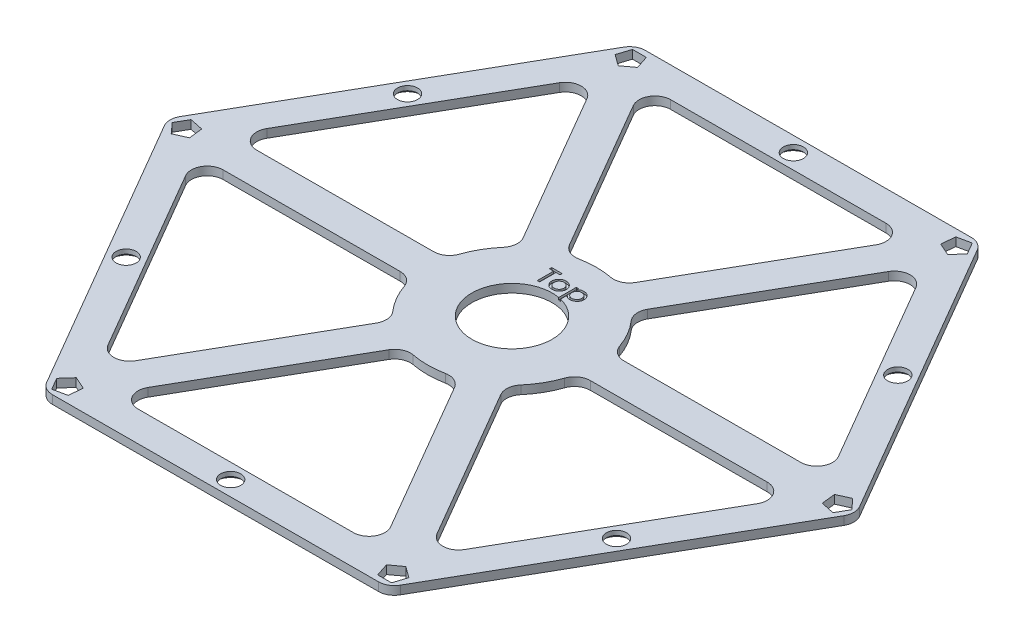
SolidWorks part; units mm, degrees
ref_plane "Front Plane" through (0, 0, 0) normal (0, 0, 1) x (1, 0, 0)
ref_plane "Top Plane" through (0, 0, 0) normal (0, 1, 0) x (1, 0, 0)
ref_plane "Right Plane" through (0, 0, 0) normal (1, 0, 0) x (0, 0, -1)
sketch "Sketch1" plane through (0, 0, 0) normal (0, 1, 0) x (1, 0, 0)
  line L0 (-31.0118, 53.34) -> (-30.9795, 42.6969) construction
  line L1 (-32.6705, 56.1929) -> (-64.9997, -0.197)
  line L2 (-64.9997, -0.197) -> (-32.3292, -56.3899)
  line L3 (-32.3292, -56.3899) -> (32.6705, -56.1929)
  line L4 (32.6705, -56.1929) -> (64.9997, 0.197)
  line L5 (64.9997, 0.197) -> (32.3292, 56.3899)
  line L6 (32.3292, 56.3899) -> (-32.6705, 56.1929)
  line L7 (-31.1934, 47.2773) -> (-56.5594, 3.0329)
  line L8 (-56.54, -3.3757) -> (-30.9063, -47.4655)
  line L9 (-25.3466, -50.6529) -> (25.6532, -50.4984)
  line L10 (31.1934, -47.2773) -> (56.5594, -3.0329)
  line L11 (56.54, 3.3757) -> (30.9063, 47.4655)
  line L12 (25.3466, 50.6529) -> (-25.6532, 50.4984)
  line L13 (-31.0118, 53.34) -> (-61.6997, -0.187) construction
  line L14 (-61.6997, -0.187) -> (-30.6879, -53.527) construction
  line L15 (-30.6879, -53.527) -> (31.0118, -53.34) construction
  line L16 (31.0118, -53.34) -> (61.6997, 0.187) construction
  line L17 (61.6997, 0.187) -> (30.6879, 53.527) construction
  line L18 (30.6879, 53.527) -> (-31.0118, 53.34) construction
  line L50 (28.7645, 52.4087) -> (31.1571, 51.3521)
  line L51 (-31.0051, 51.1151) -> (-28.8937, 52.6589)
  line L52 (-28.8937, 52.6589) -> (-29.7095, 55.144)
  line L58 (-31.1934, 47.2773) -> (-10.6492, 11.9413)
  line L60 (25.3466, 50.6529) -> (5.0169, 15.1931)
  line L66 (56.54, 3.3757) -> (15.6661, 3.2518)
  line L72 (31.1934, -47.2773) -> (10.6492, -11.9413)
  line L78 (-25.3466, -50.6529) -> (-5.0169, -15.1931)
  line L84 (-56.54, -3.3757) -> (-15.6661, -3.2518)
  line L89 (-5.1089, 15.1624) -> (-25.6532, 50.4984)
  line L91 (-29.7095, 55.144) -> (-32.325, 55.136)
  line L92 (10.5766, 12.0056) -> (30.9063, 47.4655)
  line L94 (-32.325, 55.136) -> (-33.1257, 52.6461)
  line L95 (15.6855, -3.1568) -> (56.5594, -3.0329)
  line L97 (-33.1257, 52.6461) -> (-31.0051, 51.1151)
  line L98 (5.1089, -15.1624) -> (25.6532, -50.4984)
  line L100 (31.1571, 51.3521) -> (32.9013, 53.3012)
  line L101 (-10.5766, -12.0056) -> (-30.9063, -47.4655)
  line L103 (32.9013, 53.3012) -> (31.5867, 55.5623)
  line L104 (-15.6855, 3.1568) -> (-56.5594, 3.0329)
  line L106 (31.5867, 55.5623) -> (29.03, 55.0108)
  line L107 (29.03, 55.0108) -> (28.7645, 52.4087)
  line L108 (59.7695, 1.2936) -> (60.0508, -1.3068)
  line L109 (60.0508, -1.3068) -> (62.6108, -1.8428)
  line L110 (62.6108, -1.8428) -> (63.9117, 0.4263)
  line L111 (63.9117, 0.4263) -> (62.1557, 2.3647)
  line L112 (62.1557, 2.3647) -> (59.7695, 1.2936)
  line L113 (31.0051, -51.1151) -> (28.8937, -52.6589)
  line L114 (28.8937, -52.6589) -> (29.7095, -55.144)
  line L115 (29.7095, -55.144) -> (32.325, -55.136)
  line L116 (32.325, -55.136) -> (33.1257, -52.6461)
  line L117 (33.1257, -52.6461) -> (31.0051, -51.1151)
  line L118 (-28.7645, -52.4087) -> (-31.1571, -51.3521)
  line L119 (-31.1571, -51.3521) -> (-32.9013, -53.3012)
  line L120 (-32.9013, -53.3012) -> (-31.5867, -55.5623)
  line L121 (-31.5867, -55.5623) -> (-29.03, -55.0108)
  line L122 (-29.03, -55.0108) -> (-28.7645, -52.4087)
  line L123 (-59.7695, -1.2936) -> (-60.0508, 1.3068)
  line L124 (-60.0508, 1.3068) -> (-62.6108, 1.8428)
  line L125 (-62.6108, 1.8428) -> (-63.9117, -0.4263)
  line L126 (-63.9117, -0.4263) -> (-62.1557, -2.3647)
  line L127 (-62.1557, -2.3647) -> (-59.7695, -1.2936)
  circle A0 centre (0, 0) radius 56.2917 construction
  circle A1 centre (0, 0) radius 50.5759 construction
  circle A2 centre (0, 0) radius 53.4338 construction
  circle A3 centre (-31.0118, 53.34) radius 1.8 construction
  arc A4 (-10.6492, 11.9413) -> (-15.6855, 3.1568) centre (0, 0) ccw
  arc A5 (5.0169, 15.1931) -> (-5.1089, 15.1624) centre (0, 0) ccw
  arc A6 (15.6661, 3.2518) -> (10.5766, 12.0056) centre (0, 0) ccw
  arc A7 (10.6492, -11.9413) -> (15.6855, -3.1568) centre (0, 0) ccw
  arc A8 (-5.0169, -15.1931) -> (5.1089, -15.1624) centre (0, 0) ccw
  arc A9 (-15.6661, -3.2518) -> (-10.5766, -12.0056) centre (0, 0) ccw
  circle A10 centre (-46.3558, 26.5765) radius 1.9
  circle A11 centre (-0.1619, 53.4335) radius 1.9
  circle A12 centre (46.1938, 26.857) radius 1.9
  circle A13 centre (46.3558, -26.5765) radius 1.9
  circle A14 centre (0.1619, -53.4335) radius 1.9
  circle A15 centre (-46.1938, -26.857) radius 1.9
  point P53 (0, 0)
  point P58 (-0.0078, -0.0152)
  point P70 (0, 0)
  point P87 (0, 0)
  dimension "D5" = 6
  dimension "D1" = 65
  dimension "D2" = 30
  dimension "D3" = 3.3
  dimension "D4" = 6
  dimension "D7" = 6
extrude "Boss-Extrude1" add sketch "Sketch1" along normal blind 1.6
fillet "Fillet1" radius 3 6 edges at (-64.9997, 0.8, 0.197) (-32.3292, 0.8, 56.3899) (32.6705, 0.8, 56.1929) (64.9997, 0.8, -0.197) (32.3292, 0.8, -56.3899) (-32.6705, 0.8, -56.1929)
sketch "Sketch2" plane through (0, 0, 0) normal (0, 1, 0) x (1, 0, 0)
fillet "Fillet2" radius 3 24 edges at (-25.3466, 0.8, 50.6529) (31.1934, 0.8, 47.2773) (25.6532, 0.8, 50.4984) (-30.9063, 0.8, 47.4655) (-56.54, 0.8, 3.3757) (-15.6661, 0.8, 3.2518) (-10.5766, 0.8, 12.0056) (-31.1934, 0.8, -47.2773) (-56.5594, 0.8, -3.0329) (-15.6855, 0.8, -3.1568) (-10.6492, 0.8, -11.9413) (-25.6532, 0.8, -50.4984) (25.3466, 0.8, -50.6529) (56.54, 0.8, -3.3757) (56.5594, 0.8, 3.0329) (30.9063, 0.8, -47.4655) (-5.0169, 0.8, 15.1931) (5.1089, 0.8, 15.1624) (10.6492, 0.8, 11.9413) (15.6855, 0.8, 3.1568) (15.6661, 0.8, -3.2518) (10.5766, 0.8, -12.0056) (5.0169, 0.8, -15.1931) (-5.1089, 0.8, -15.1624)
ref_plane "Plane1" through (0, 3.6, 0) normal (0, 1, 0) x (1, 0, 0)
sketch "Sketch3" plane through (0, 3.6, 0) normal (0, 1, 0) x (1, 0, 0)
  circle A0 centre (0, 0) radius 7.6
extrude "Cut-Extrude1" cut sketch "Sketch3" against normal blind 10
chamfer "Chamfer1" distance 0.75 angle 48 6 edges at (0.1619, 0, 55.3335) (-46.1938, 0, 28.757) (-46.3558, 0, -24.6765) (46.3558, 0, 28.4765) (46.1938, 0, -24.957) (-0.1619, 0, -51.5335)
ref_plane "Plane2" through (0, 1.6, 0) normal (0, 1, 0) x (1, 0, 0)
sketch "Sketch4" plane through (0, 1.6, 0) normal (0, 1, 0) x (1, 0, 0)
  line L0 (-11.0192, 8.222) -> (11.0192, 8.222) construction
  text T0 "<b>Top</b>"
extrude "Cut-Extrude2" cut sketch "Sketch4" against normal blind 0.4
scale "Scale1" scale about centroid uniform scaling yes scale factor 1.15
